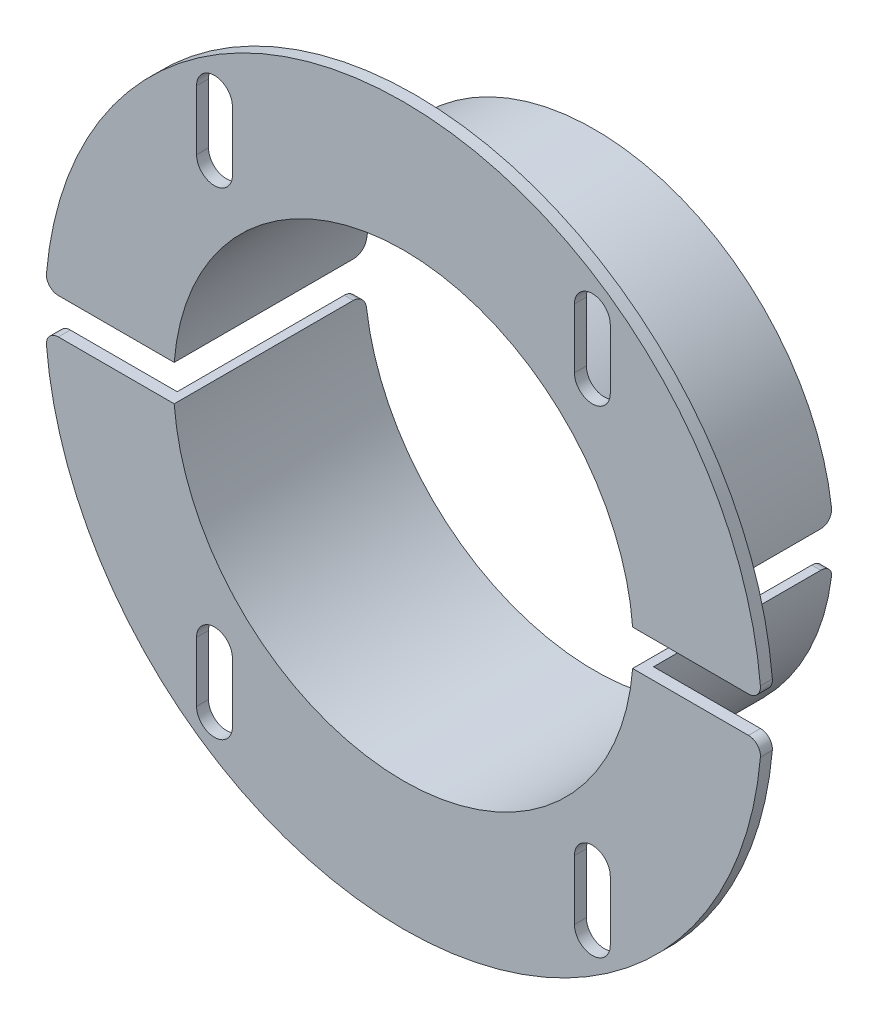
SolidWorks part; units mm, degrees
ref_plane "前视基准面" through (0, 0, 0) normal (0, 0, 1) x (1, 0, 0)
ref_plane "上视基准面" through (0, 0, 0) normal (0, 1, 0) x (1, 0, 0)
ref_plane "右视基准面" through (0, 0, 0) normal (1, 0, 0) x (0, 0, -1)
sketch "草图1" plane through (0, 0, 0) normal (0, 0, 1) x (1, 0, 0)
  circle A0 centre (0, 0) radius 40
  circle A1 centre (0, 0) radius 38.5
  dimension "D1" = 80
  dimension "D2" = 77
extrude "凸台-拉伸1" add sketch "草图1" along normal blind 30
sketch "草图3" plane through (0, 0, 30) normal (0, 0, 1) x (1, 0, 0)
  circle A0 centre (0, 0) radius 60
  circle A1 centre (0, 0) radius 38.5
  dimension "D1" = 120
  dimension "D2" = 77
extrude "凸台-拉伸2" add sketch "草图3" along normal blind 2
sketch "草图4" plane through (0, 0, 30) normal (0, 0, -1) x (-1, 0, 0)
  line L0 (-31.6386, -45) -> (-31.6386, -35) construction
  line L1 (-31.6386, -40) -> (31.6386, -40) construction
  line L2 (-31.6386, -40) -> (-31.6386, 40) construction
  line L3 (-31.6386, 40) -> (31.6386, 40) construction
  line L4 (31.6386, -40) -> (31.6386, 40) construction
  line L5 (-31.6386, -40) -> (31.6386, 40) construction
  line L6 (-31.6386, 40) -> (31.6386, -40) construction
  line L7 (-34.6386, -45) -> (-34.6386, -35)
  line L8 (-28.6386, -45) -> (-28.6386, -35)
  line L9 (31.6386, -45) -> (31.6386, -35) construction
  line L10 (28.6386, -45) -> (28.6386, -35)
  line L11 (34.6386, -45) -> (34.6386, -35)
  line L12 (31.6386, 35) -> (31.6386, 45) construction
  line L13 (28.6386, 35) -> (28.6386, 45)
  line L14 (34.6386, 35) -> (34.6386, 45)
  line L15 (-31.6386, 35) -> (-31.6386, 45) construction
  line L16 (-34.6386, 35) -> (-34.6386, 45)
  line L17 (-28.6386, 35) -> (-28.6386, 45)
  circle A0 centre (0, 0) radius 51 construction
  arc A1 (-34.6386, -45) -> (-28.6386, -45) centre (-31.6386, -45) ccw
  arc A2 (-28.6386, -35) -> (-34.6386, -35) centre (-31.6386, -35) ccw
  arc A3 (28.6386, -45) -> (34.6386, -45) centre (31.6386, -45) ccw
  arc A4 (34.6386, -35) -> (28.6386, -35) centre (31.6386, -35) ccw
  arc A5 (28.6386, 35) -> (34.6386, 35) centre (31.6386, 35) ccw
  arc A6 (34.6386, 45) -> (28.6386, 45) centre (31.6386, 45) ccw
  arc A7 (-34.6386, 35) -> (-28.6386, 35) centre (-31.6386, 35) ccw
  arc A8 (-28.6386, 45) -> (-34.6386, 45) centre (-31.6386, 45) ccw
  point P9 (-31.6386, -40)
  point P15 (31.6386, -40)
  point P22 (31.6386, 40)
  point P29 (-31.6386, 40)
  dimension "D1" = 102
  dimension "D3" = 3
  dimension "D2" = 80
  dimension "D4" = 10
extrude "切除-拉伸3" cut sketch "草图4" against normal through all
sketch "草图2" plane through (0, 0, 0) normal (0, 0, -1) x (-1, 0, 0)
  line L1 (100, 3) -> (-100, 3)
  line L2 (100, 3) -> (100, -3)
  line L3 (100, -3) -> (-100, -3)
  line L4 (-100, 3) -> (-100, -3)
  line L5 (100, 3) -> (-100, -3) construction
  line L6 (100, -3) -> (-100, 3) construction
  point P0 (0, 0)
  dimension "D1" = 6
  dimension "D2" = 200
extrude "切除-拉伸2" cut sketch "草图2" against normal blind 2000
fillet "圆角1" radius 2 4 edges at (-39.1351, -3, 0) (39.1351, -3, 0) (-59.925, -3, 31) (59.925, -3, 31)
fillet "圆角2" radius 2 4 edges at (59.925, 3, 31) (-59.925, 3, 31) (-39.1351, 3, 0) (39.1351, 3, 0)
